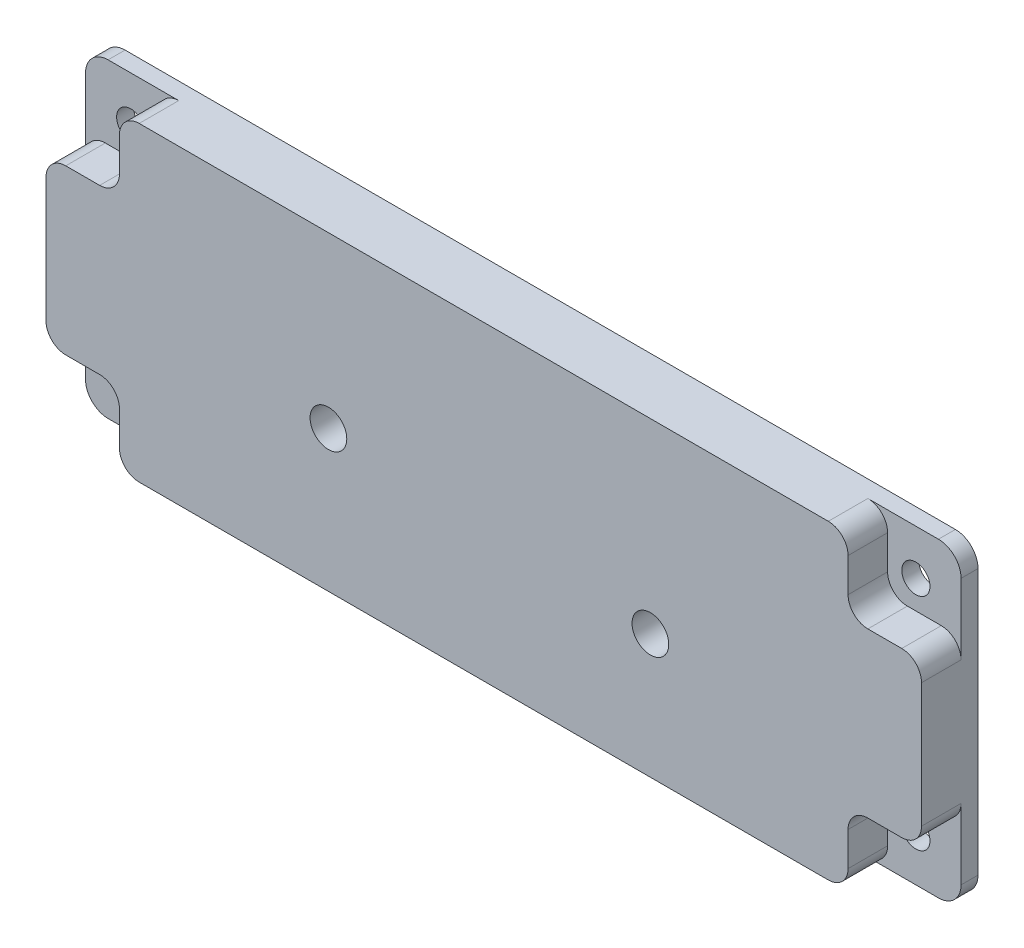
SolidWorks part; units mm, degrees
ref_plane "Front Plane" through (0, 0, 0) normal (0, 0, 1) x (1, 0, 0)
ref_plane "Top Plane" through (0, 0, 0) normal (0, 1, 0) x (1, 0, 0)
ref_plane "Right Plane" through (0, 0, 0) normal (1, 0, 0) x (0, 0, -1)
sketch "Sketch1" plane through (0, 0, 0) normal (0, 0, 1) x (1, 0, 0)
  line L1 (-73.7476, 33.9217) -> (73.2524, 33.9217)
  line L2 (-77.7476, 29.9217) -> (-77.7476, -17.0783)
  line L3 (-73.7476, -21.0783) -> (73.2524, -21.0783)
  line L4 (77.2524, 29.9217) -> (77.2524, -17.0783)
  arc A0 (73.2524, 33.9217) -> (77.2524, 29.9217) centre (73.2524, 29.9217) cw
  arc A1 (77.2524, -17.0783) -> (73.2524, -21.0783) centre (73.2524, -17.0783) cw
  arc A2 (-73.7476, -21.0783) -> (-77.7476, -17.0783) centre (-73.7476, -17.0783) cw
  arc A3 (-77.7476, 29.9217) -> (-73.7476, 33.9217) centre (-73.7476, 29.9217) cw
  circle A4 centre (-27.7476, 3.9217) radius 3.25
  circle A5 centre (29.2524, 0.9217) radius 3.25
  point P6 (77.2524, 33.9217)
  point P11 (-77.7476, -21.0783)
  point P14 (-77.7476, 33.9217)
  dimension "D3" = 4
  dimension "D6" = 6.5
  dimension "D9" = 6.5
  dimension "D1" = 155
  dimension "D2" = 55
  dimension "D4" = 50
  dimension "D5" = 30
  dimension "D7" = 33
  dimension "D8" = 107
extrude "Boss-Extrude1" add sketch "Sketch1" along normal blind 10
sketch "Sketch2" plane through (0, 0, 10) normal (0, 0, 1) x (1, 0, 0)
  line L0 (-77.7476, 29.9217) -> (-77.7476, -17.0783) construction
  line L1 (-77.7476, 20.9217) -> (-68.2476, 20.9217)
  line L2 (-77.7476, 20.9217) -> (-77.7476, 33.9217)
  line L3 (-77.7476, 33.9217) -> (-64.7476, 33.9217)
  line L4 (-64.7476, 24.4217) -> (-64.7476, 33.9217)
  line L5 (73.2524, 33.9217) -> (-73.7476, 33.9217) construction
  line L6 (-73.7476, -21.0783) -> (73.2524, -21.0783) construction
  line L7 (-77.7476, -8.0783) -> (-68.2476, -8.0783)
  line L8 (-77.7476, -8.0783) -> (-77.7476, -21.0783)
  line L9 (-77.7476, -21.0783) -> (-64.7476, -21.0783)
  line L10 (-64.7476, -11.5783) -> (-64.7476, -21.0783)
  line L11 (77.2524, -17.0783) -> (77.2524, 29.9217) construction
  line L12 (64.2524, -21.0783) -> (77.2524, -21.0783)
  line L13 (64.2524, -21.0783) -> (64.2524, -11.5783)
  line L14 (67.7524, -8.0783) -> (77.2524, -8.0783)
  line L15 (77.2524, -21.0783) -> (77.2524, -8.0783)
  line L17 (77.2524, 20.9217) -> (67.7524, 20.9217)
  line L18 (77.2524, 20.9217) -> (77.2524, 33.9217)
  line L19 (77.2524, 33.9217) -> (64.2524, 33.9217)
  line L20 (64.2524, 24.4217) -> (64.2524, 33.9217)
  arc A0 (-68.2476, -8.0783) -> (-64.7476, -11.5783) centre (-68.2476, -11.5783) cw
  arc A1 (64.2524, -11.5783) -> (67.7524, -8.0783) centre (67.7524, -11.5783) cw
  arc A2 (67.7524, 20.9217) -> (64.2524, 24.4217) centre (67.7524, 24.4217) cw
  arc A3 (-64.7476, 24.4217) -> (-68.2476, 20.9217) centre (-68.2476, 24.4217) cw
  point P26 (-64.7476, -8.0783)
  point P29 (64.2524, -8.0783)
  point P32 (64.2524, 20.9217)
  point P35 (-64.7476, 20.9217)
  dimension "D9" = 3.5
  dimension "D1" = 13
  dimension "D2" = 13
  dimension "D3" = 13
  dimension "D4" = 13
  dimension "D5" = 13
  dimension "D6" = 13
  dimension "D7" = 13
  dimension "D8" = 13
extrude "Cut-Extrude1" cut sketch "Sketch2" against normal blind 7
sketch "Sketch3" plane through (0, 0, 3) normal (0, 0, 1) x (1, 0, 0)
  line L0 (-64.7476, 24.4217) -> (-64.7476, 33.9217) construction
  line L1 (-77.7476, 20.9217) -> (-68.2476, 20.9217) construction
  line L2 (64.2524, 33.9217) -> (64.2524, 24.4217) construction
  line L3 (67.7524, 20.9217) -> (77.2524, 20.9217) construction
  line L4 (77.2524, -8.0783) -> (67.7524, -8.0783) construction
  line L6 (64.2524, -11.5783) -> (64.2524, -21.0783) construction
  line L7 (-64.7476, -21.0783) -> (-64.7476, -11.5783) construction
  line L8 (-68.2476, -8.0783) -> (-77.7476, -8.0783) construction
  circle A0 centre (-69.7476, 25.9217) radius 2.5
  circle A1 centre (69.2524, 25.9217) radius 2.5
  circle A2 centre (69.2524, -13.0783) radius 2.5
  circle A3 centre (-69.7476, -13.0783) radius 2.5
  point P18 (0, 0)
  point P20 (72.047, -14.7428)
  dimension "D3" = 5
  dimension "D6" = 5
  dimension "D9" = 5
  dimension "D10" = 5
  dimension "D12" = 5
  dimension "D1" = 5
  dimension "D2" = 5
  dimension "D4" = 5
  dimension "D5" = 5
  dimension "D7" = 5
  dimension "D8" = 5
  dimension "D11" = 5
extrude "Cut-Extrude2" cut sketch "Sketch3" against normal blind 10
fillet "Fillet1" radius 3.5 8 edges at (77.2524, 20.9217, 6.5) (64.2524, 33.9217, 6.5) (77.2524, -8.0783, 6.5) (64.2524, -21.0783, 6.5) (-64.7476, 33.9217, 6.5) (-77.7476, 20.9217, 6.5) (-64.7476, -21.0783, 6.5) (-77.7476, -8.0783, 6.5)
